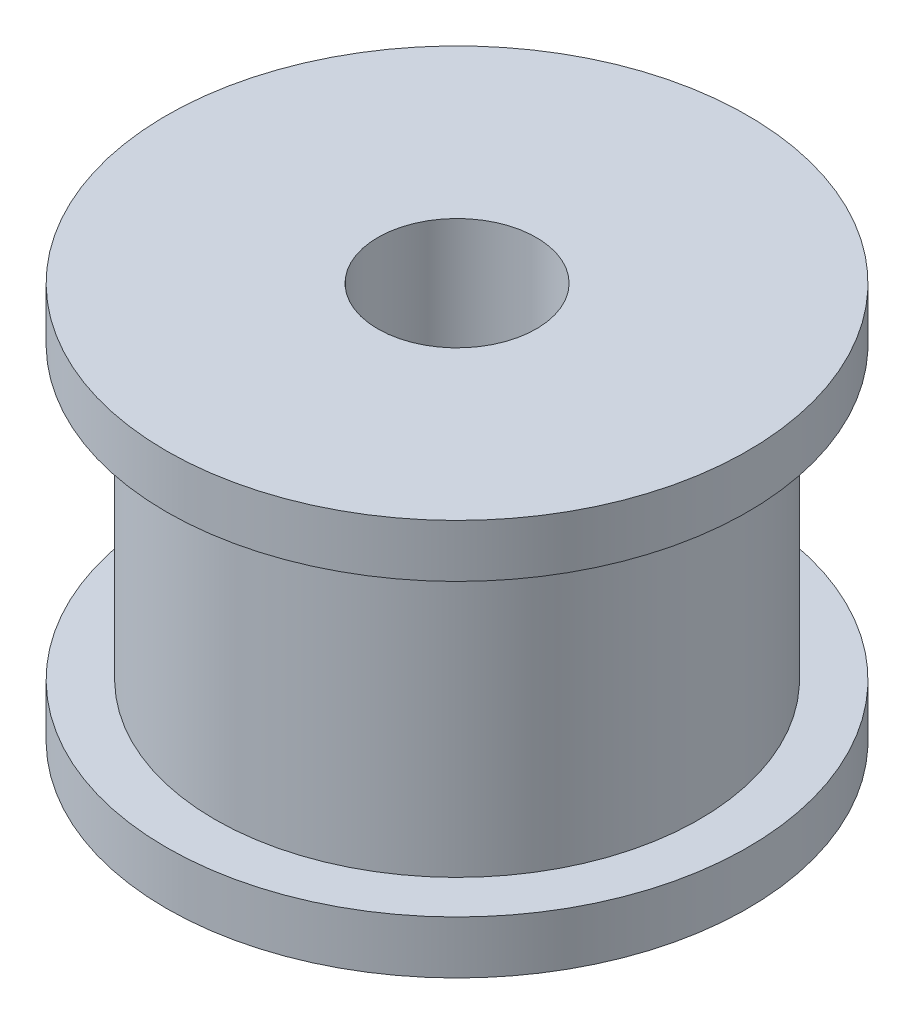
SolidWorks part; units mm, degrees
ref_plane "Front" through (0, 0, 0) normal (0, 0, 1) x (1, 0, 0)
ref_plane "Top" through (0, 0, 0) normal (0, 1, 0) x (1, 0, 0)
ref_plane "Right" through (0, 0, 0) normal (1, 0, 0) x (0, 0, -1)
sketch "草图1" plane through (0, 0, 0) normal (0, 1, 0) x (1, 0, 0)
  circle A0 centre (0, 0) radius 11
  circle A1 centre (0, 0) radius 3
  dimension "D1" = 22
  dimension "D2" = 6
extrude "凸台-拉伸1" add sketch "草图1" along normal blind 15
sketch "草图2" plane through (0, 0, 0) normal (0, 1, 0) x (1, 0, 0)
  circle A0 centre (0, 0) radius 11
  circle A1 centre (0, 0) radius 9.165
  dimension "D1" = 18.33
extrude "切除-拉伸1" cut sketch "草图2" along normal blind 11 from offset 2
